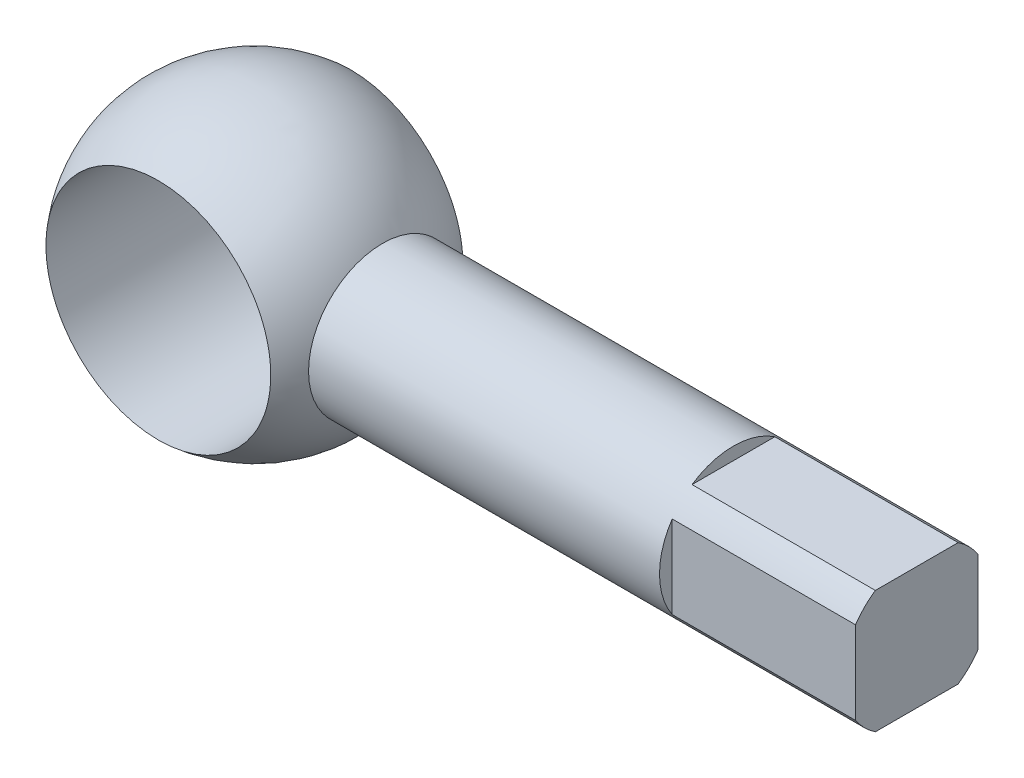
SolidWorks part; units mm, degrees
ref_plane "Front Plane" through (0, 0, 0) normal (0, 0, 1) x (1, 0, 0)
ref_plane "Top Plane" through (0, 0, 0) normal (0, 1, 0) x (1, 0, 0)
ref_plane "Right Plane" through (0, 0, 0) normal (1, 0, 0) x (0, 0, -1)
sketch "Sketch2" plane through (0, 0, 0) normal (0, 0, 1) x (1, 0, 0)
  line L0 (-25, 0) -> (26.9637, 0) construction
  line L1 (21.6506, 12.5) -> (112, 12.5)
  line L2 (112, 12.5) -> (112, 0)
  line L3 (112, 0) -> (-25, 0)
  arc A0 (-25, 0) -> (21.6506, 12.5) centre (0, 0) cw
  dimension "D1" = 25
  dimension "D2" = 12.5
  dimension "D3" = 112
revolve "Revolve2" add sketch "Sketch2" angle 360 about L0
sketch "Sketch3" plane through (0, 0, 0) normal (0, 0, 1) x (1, 0, 0)
  circle A0 centre (0, 0) radius 19
  arc A1 (21.6506, 12.5) -> (21.6506, -12.5) centre (0, 0) ccw construction
  dimension "D1" = 38
extrude "Cut-Extrude1" cut sketch "Sketch3" against normal through all both and the other way through all
sketch "Sketch4" plane through (112, 0, 0) normal (1, 0, 0) x (0, 0, -1)
  line L0 (-7, 10.3562) -> (7, 10.3562)
  circle A1 centre (0, 0) radius 12.5
  circle A2 centre (0, 0) radius 12.5
  dimension "D2" = 14
  dimension "D1" = 0
extrude "Cut-Extrude2" cut sketch "Sketch4" against normal blind 31 and the other way through all contours L0
pattern_circular "CirPattern1" count 4 over 360 about axis through (112, 0, 0) along (-1, 0, 0) of "Cut-Extrude2"
